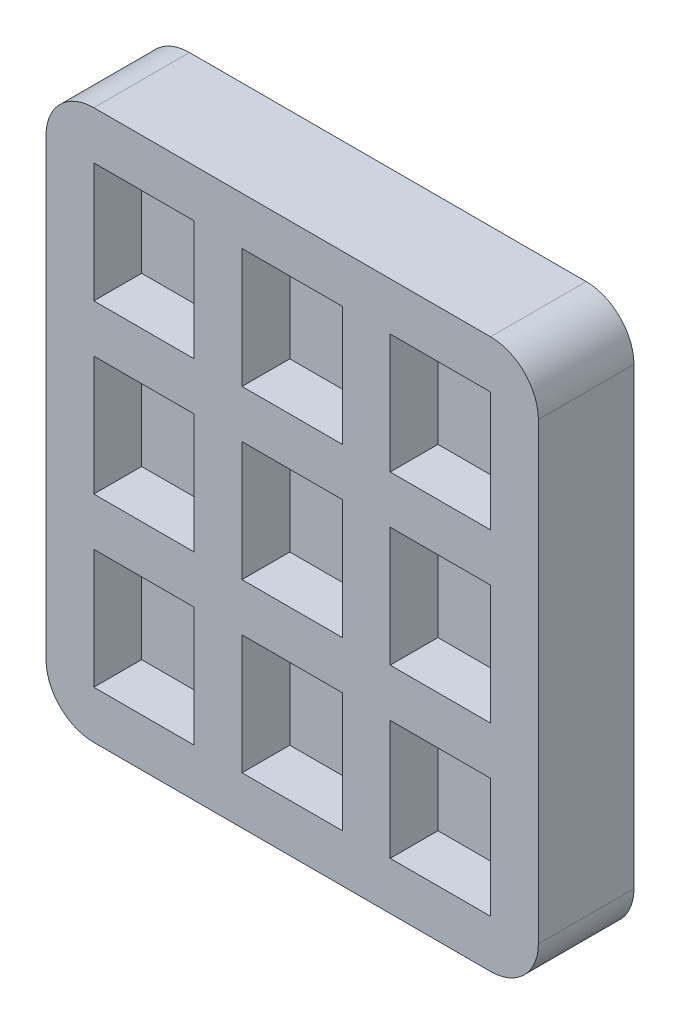
SolidWorks part; units mm, degrees
ref_plane "Front Plane" through (0, 0, 0) normal (0, 0, 1) x (1, 0, 0)
ref_plane "Top Plane" through (0, 0, 0) normal (0, 1, 0) x (1, 0, 0)
ref_plane "Right Plane" through (0, 0, 0) normal (1, 0, 0) x (0, 0, -1)
sketch "Sketch1" plane through (0, 0, 0) normal (0, 0, 1) x (1, 0, 0)
  line L1 (0, 0) -> (103, 0)
  line L2 (0, 0) -> (0, 115)
  line L3 (0, 115) -> (103, 115)
  line L4 (103, 0) -> (103, 115)
extrude "Boss-Extrude2" add sketch "Sketch1" along normal blind 20
sketch "Sketch3" plane through (0, 0, 20) normal (0, 0, 1) x (1, 0, 0)
  line L3 (10, 105) -> (10, 80)
  line L4 (10, 80) -> (31, 80)
  line L5 (31, 80) -> (31, 105)
  line L6 (31, 105) -> (10, 105)
  line L8 (41, 105) -> (41, 80)
  line L9 (41, 80) -> (62, 80)
  line L10 (62, 80) -> (62, 105)
  line L11 (62, 105) -> (41, 105)
  line L13 (72, 105) -> (72, 80)
  line L14 (72, 80) -> (93, 80)
  line L15 (93, 80) -> (93, 105)
  line L16 (93, 105) -> (72, 105)
  line L18 (10, 70) -> (10, 54.3793)
  line L19 (31, 70) -> (31, 45)
  line L20 (10, 70) -> (31, 70)
  line L21 (31, 45) -> (10, 45)
  line L22 (10, 45) -> (10, 54.3793)
  line L24 (41, 70) -> (41, 45)
  line L25 (41, 45) -> (62, 45)
  line L26 (62, 45) -> (62, 70)
  line L27 (62, 70) -> (41, 70)
  line L29 (10, 35) -> (10, 17.4627)
  line L30 (31, 35) -> (31, 10)
  line L31 (10, 35) -> (31, 35)
  line L32 (31, 10) -> (10, 10)
  line L33 (10, 10) -> (10, 17.4627)
  line L35 (41, 35) -> (41, 10)
  line L36 (41, 10) -> (62, 10)
  line L37 (62, 10) -> (62, 35)
  line L38 (62, 35) -> (41, 35)
  line L40 (72, 35) -> (72, 10)
  line L41 (72, 10) -> (93, 10)
  line L42 (93, 10) -> (93, 35)
  line L43 (93, 35) -> (72, 35)
  line L44 (72, 45) -> (93, 45)
  line L45 (93, 45) -> (93, 70)
  line L46 (93, 70) -> (72, 70)
  line L47 (72, 70) -> (72, 45)
extrude "Cut-Extrude1" cut sketch "Sketch3" against normal blind 10
sketch "Sketch4" plane through (0, 0, 20) normal (0, 0, 1) x (1, 0, 0)
  line L4 (0, 105) -> (0, 115)
  line L5 (0, 115) -> (10, 115)
  line L6 (93, 115) -> (103, 115)
  line L7 (103, 115) -> (103, 105)
  line L8 (103, 10) -> (103, 0)
  line L9 (103, 0) -> (93, 0)
  line L10 (10, 0) -> (0, 0)
  line L11 (0, 0) -> (0, 10)
  arc A0 (0, 10) -> (10, 0) centre (10, 10) ccw
  arc A1 (93, 0) -> (103, 10) centre (93, 10) ccw
  arc A2 (103, 105) -> (93, 115) centre (93, 105) ccw
  arc A3 (10, 115) -> (0, 105) centre (10, 105) ccw
  point P10 (0, 0)
  point P13 (103, 0)
  point P16 (103, 115)
  point P19 (0, 115)
extrude "Cut-Extrude2" cut sketch "Sketch4" against normal blind 46
